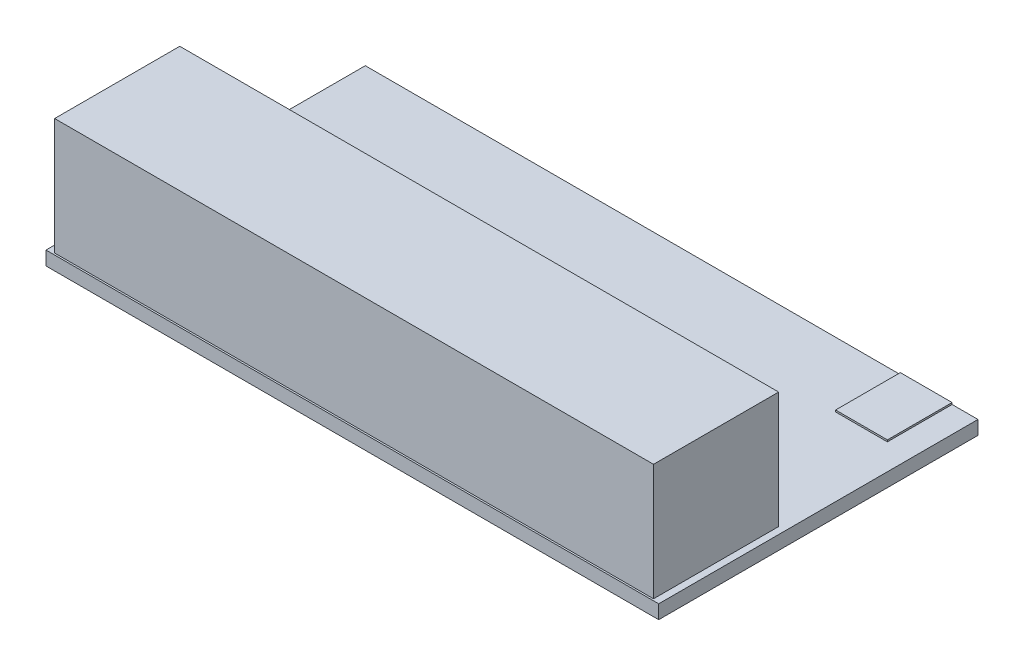
SolidWorks part; units mm, degrees
ref_plane "Front Plane" through (0, 0, 0) normal (0, 0, 1) x (1, 0, 0)
ref_plane "Top Plane" through (0, 0, 0) normal (0, 1, 0) x (1, 0, 0)
ref_plane "Right Plane" through (0, 0, 0) normal (1, 0, 0) x (0, 0, -1)
sketch "Sketch1" plane through (0, 0, 0) normal (0, 1, 0) x (1, 0, 0)
  line L1 (0, 0) -> (71, 0)
  line L2 (0, 0) -> (0, 37)
  line L3 (0, 37) -> (71, 37)
  line L4 (71, 0) -> (71, 37)
  dimension "D1" = 71
  dimension "D2" = 37
extrude "Boss-Extrude1" add sketch "Sketch1" along normal blind 1.6
sketch "Sketch2" plane through (0, 1.6, 0) normal (0, 1, 0) x (1, 0, 0)
  line L0 (0, 0) -> (71, 0) construction
  line L1 (0.8, 14.7) -> (70.2, 14.7)
  line L2 (0.8, 14.7) -> (0.8, 0.2)
  line L3 (0.8, 0.2) -> (70.2, 0.2)
  line L4 (70.2, 14.7) -> (70.2, 0.2)
  line L5 (71, 0) -> (71, 37) construction
  line L6 (35.5, 0) -> (35.5, 0.2) construction
  dimension "D1" = 14.5
  dimension "D2" = 69.4
  dimension "D3" = 0.2
extrude "Boss-Extrude2" add sketch "Sketch2" along normal blind 13.5
sketch "Sketch3" plane through (0, 1.6, 0) normal (0, 1, 0) x (1, 0, 0)
  line L0 (71, 37) -> (0, 37) construction
  line L1 (68, 29.5) -> (62, 29.5)
  line L2 (68, 29.5) -> (68, 37)
  line L3 (68, 37) -> (62, 37)
  line L4 (62, 29.5) -> (62, 37)
  line L5 (71, 0) -> (71, 37) construction
  dimension "D1" = 6
  dimension "D2" = 7.5
  dimension "D3" = 3
extrude "Boss-Extrude3" add sketch "Sketch3" along normal blind 0.2
